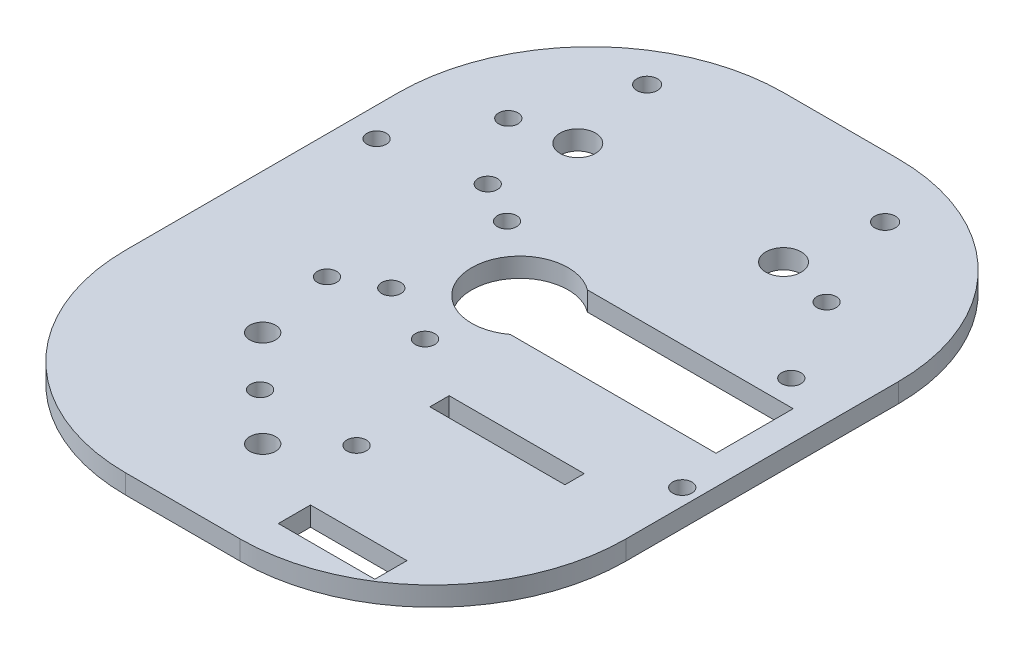
SolidWorks part; units mm, degrees
ref_plane "Plan de face" through (0, 0, 0) normal (0, 0, 1) x (1, 0, 0)
ref_plane "Plan de dessus" through (0, 0, 0) normal (0, 1, 0) x (1, 0, 0)
ref_plane "Plan de droite" through (0, 0, 0) normal (1, 0, 0) x (0, 0, -1)
sketch "Sketch1" plane through (0, 0, 0) normal (0, 1, 0) x (1, 0, 0)
  line L0 (-16, 25) -> (16, 25) construction
  line L1 (15, -25) -> (-15, -25) construction
  line L20 (0, -10) -> (0, -40) construction
  line L22 (41.0327, -54.5472) -> (-36.7606, -54.5472)
  line L23 (41.0327, -54.5472) -> (41.0327, 47.8172)
  line L24 (41.0327, 47.8172) -> (-36.7606, 47.8172)
  line L25 (-36.7606, -54.5472) -> (-36.7606, 47.8172)
  circle A5 centre (0, 25) radius 4
  circle A6 centre (0, -25) radius 4
  circle A14 centre (-16, 25) radius 2.75
  circle A15 centre (16, 25) radius 2.75
  circle A17 centre (-15, -25) radius 2
  circle A18 centre (0, 0) radius 7.5
  circle A19 centre (0, -40) radius 2
  point P4 (0, 0)
  point P26 (0, 25)
  point P30 (0, -25)
  dimension "D2" = 5.5
  dimension "D3" = 25
  dimension "D4" = 25
  dimension "D7" = 2
  dimension "D8" = 8
  dimension "D5" = 15
  dimension "D6" = 15
  dimension "D14" = 8
  dimension "D15" = 5.5
  dimension "D17" = 4
  dimension "D18" = 32
extrude "Boss-Extrude1" add sketch "Sketch1" along normal blind 3
sketch "Sketch2" plane through (0, 3, 0) normal (0, 1, 0) x (1, 0, 0)
  line L0 (0, 0) -> (0, -30) construction
  line L1 (0, 0) -> (-25.9808, 15) construction
  line L2 (-28.4808, 10.6699) -> (-23.4808, 19.3301) construction
  line L3 (-28.4808, 10.6699) -> (-33.6769, 13.6699) construction
  line L4 (5, -30) -> (-5, -30) construction
  line L5 (5, -30) -> (5, -36) construction
  line L6 (5, -36) -> (-5, -36) construction
  line L7 (-5, -30) -> (-5, -36) construction
  line L8 (-33.6769, 13.6699) -> (-28.6769, 22.3301) construction
  line L9 (-23.4808, 19.3301) -> (-28.6769, 22.3301) construction
  line L10 (0, 0) -> (25.9808, 15) construction
  line L11 (23.4808, 19.3301) -> (28.4808, 10.6699) construction
  line L12 (23.4808, 19.3301) -> (28.6769, 22.3301) construction
  line L13 (28.6769, 22.3301) -> (33.6769, 13.6699) construction
  line L14 (28.4808, 10.6699) -> (33.6769, 13.6699) construction
  circle A0 centre (7.5, -32.9056) radius 1.5
  circle A1 centre (-7.5, -32.9056) radius 1.5
  circle A2 centre (-32.2471, 9.9576) radius 1.5
  circle A3 centre (-24.7471, 22.948) radius 1.5
  circle A4 centre (24.7471, 22.948) radius 1.5
  circle A5 centre (32.2471, 9.9576) radius 1.5
  point P9 (0, -30)
  dimension "D1" = 3
  dimension "D2" = 7.5
  dimension "D3" = 30
  dimension "D4" = 3
  dimension "D6" = 10
  dimension "D7" = 6
extrude "Cut-Extrude1" cut sketch "Sketch2" against normal through all both and the other way through all
sketch "Sketch3" plane through (0, 3, 0) normal (0, 1, 0) x (1, 0, 0)
  line L0 (0, 0) -> (59.573, 0) construction
  line L1 (0.5, -6) -> (36.5, -6)
  line L2 (0.5, -6) -> (0.5, 6)
  line L3 (36.5, -6) -> (36.5, 6)
  line L4 (0.5, 6) -> (36.5, 6)
  line L5 (0.5, -6) -> (36.5, 6) construction
  line L6 (36.5, -6) -> (0.5, 6) construction
  line L7 (18.5, 33.9183) -> (18.5, 2.0157) construction
  line L8 (8, -22) -> (8, -19)
  line L9 (8, -22) -> (29, -22)
  line L10 (8, -19) -> (29, -19)
  line L11 (29, -22) -> (29, -19)
  line L12 (8, -22) -> (29, -19) construction
  line L13 (8, -19) -> (29, -22) construction
  line L15 (26.9346, -44.5) -> (11.9346, -44.5)
  line L16 (26.9346, -44.5) -> (26.9346, -49.5)
  line L17 (26.9346, -49.5) -> (11.9346, -49.5)
  line L18 (11.9346, -44.5) -> (11.9346, -49.5)
  circle A1 centre (38.5, -13.2513) radius 1.5
  circle A2 centre (-1.5, -13.2513) radius 1.5
  point P4 (18.5, 0)
  point P15 (18.5, -20.5)
  dimension "D3" = 3
  dimension "D8" = 15
  dimension "D1" = 36
  dimension "D2" = 12
  dimension "D4" = 18.5
  dimension "D5" = 20
  dimension "D6" = 21
  dimension "D7" = 13
  dimension "D9" = 5
  dimension "D10" = 3
  dimension "D11" = 22.5
extrude "Cut-Extrude2" cut sketch "Sketch3" against normal through all both and the other way through all
sketch "Sketch4" plane through (0, 3, 0) normal (0, 1, 0) x (1, 0, 0)
  line L0 (-11, 9) -> (-11, -9) construction
  line L1 (36.5, -6) -> (36.5, 6) construction
  line L2 (-11, 0) -> (36.5, 0) construction
  circle A0 centre (-11, 9) radius 1.5
  circle A1 centre (-11, -9) radius 1.5
  dimension "D1" = 3
  dimension "D2" = 3
  dimension "D3" = 11
  dimension "D4" = 18
extrude "Cut-Extrude3" cut sketch "Sketch4" against normal through all both and the other way through all
sketch "Sketch5" plane through (0, 3, 0) normal (0, 1, 0) x (1, 0, 0)
  line L0 (18.5, 38.2865) -> (-18.5, 38.2865) construction
  line L2 (20.5074, 44.7865) -> (-20.5909, 44.7865) construction
  line L3 (20.5074, 44.7865) -> (20.5074, 31.7865) construction
  line L4 (20.5074, 31.7865) -> (-20.5909, 31.7865) construction
  line L5 (-20.5909, 44.7865) -> (-20.5909, 31.7865) construction
  circle A0 centre (18.5, 38.2865) radius 1.6
  circle A1 centre (-18.5, 38.2865) radius 1.6
  point P4 (0, 38.2865)
  point P5 (20.5074, 38.2865)
  dimension "D1" = 3.2
  dimension "D2" = 3.2
  dimension "D3" = 37
  dimension "D4" = 13
extrude "Cut-Extrude4" cut sketch "Sketch5" against normal through all both and the other way through all contours A0
fillet "Fillet1" radius 30 4 edges at (41.0327, 1.5, 54.5472) (-36.7606, 1.5, 54.5472) (-36.7606, 1.5, -47.8172) (41.0327, 1.5, -47.8172)
sketch "Sketch6" plane through (0, 3, 0) normal (0, 1, 0) x (1, 0, 0)
  line L0 (-5, -5) -> (-5, 5) construction
  circle A0 centre (-17.5, 12.5) radius 1.5
  circle A1 centre (-17.5, -12.5) radius 1.5
  dimension "D1" = 3
  dimension "D2" = 3
  dimension "D3" = 12.5
  dimension "D4" = 12.5
  dimension "D5" = 12.5
extrude "Cut-Extrude5" cut sketch "Sketch6" against normal through all both and the other way through all contours A0 | A1
